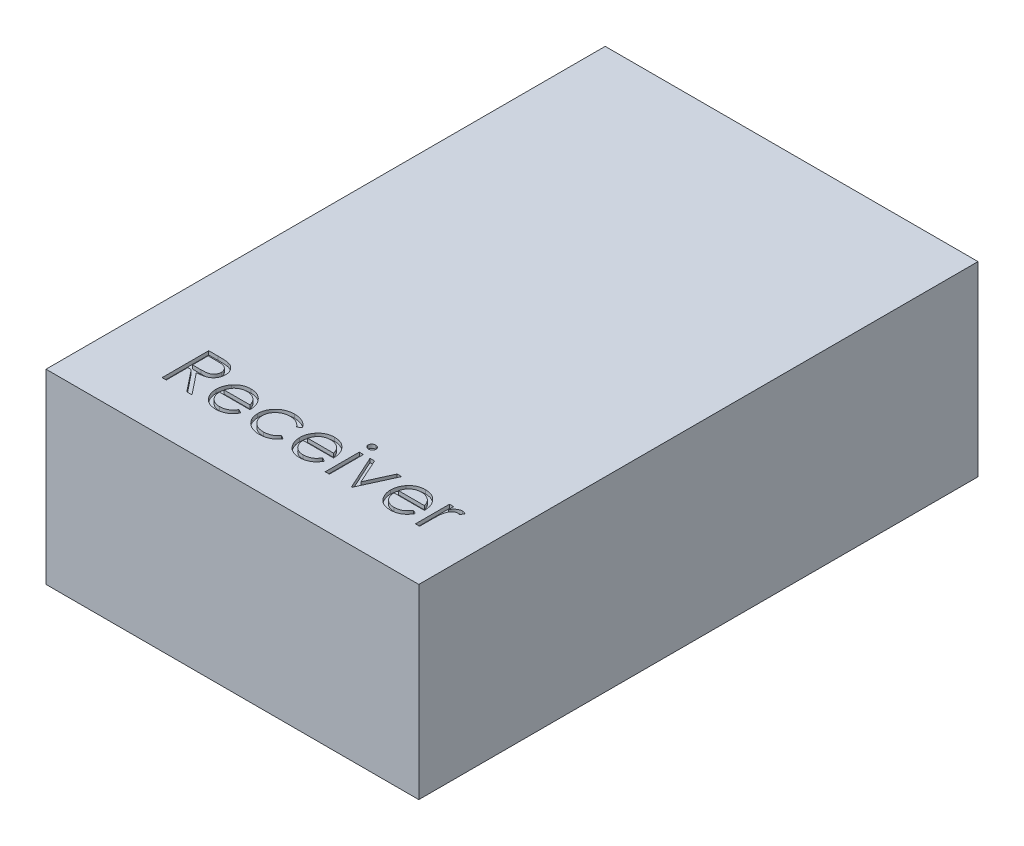
SolidWorks part; units mm, degrees
ref_plane "Front Plane" through (0, 0, 0) normal (0, 0, 1) x (1, 0, 0)
ref_plane "Top Plane" through (0, 0, 0) normal (0, 1, 0) x (1, 0, 0)
ref_plane "Right Plane" through (0, 0, 0) normal (1, 0, 0) x (0, 0, -1)
sketch "Sketch1" plane through (0, 0, 0) normal (1, 0, 0) x (0, 0, -1)
  line L1 (0, 0) -> (38.1, 0)
  line L2 (0, 0) -> (0, 12.7)
  line L3 (0, 12.7) -> (38.1, 12.7)
  line L4 (38.1, 0) -> (38.1, 12.7)
  dimension "D1" = 38.1
  dimension "D2" = 12.7
extrude "Extrude1" add sketch "Sketch1" along normal mid plane 25.4
sketch "Sketch4" plane through (0, 12.7, 0) normal (0, 1, 0) x (1, 0, 0)
  text T0 "Receiver"
extrude "Extrude2" cut sketch "Sketch4" against normal blind 0.254
